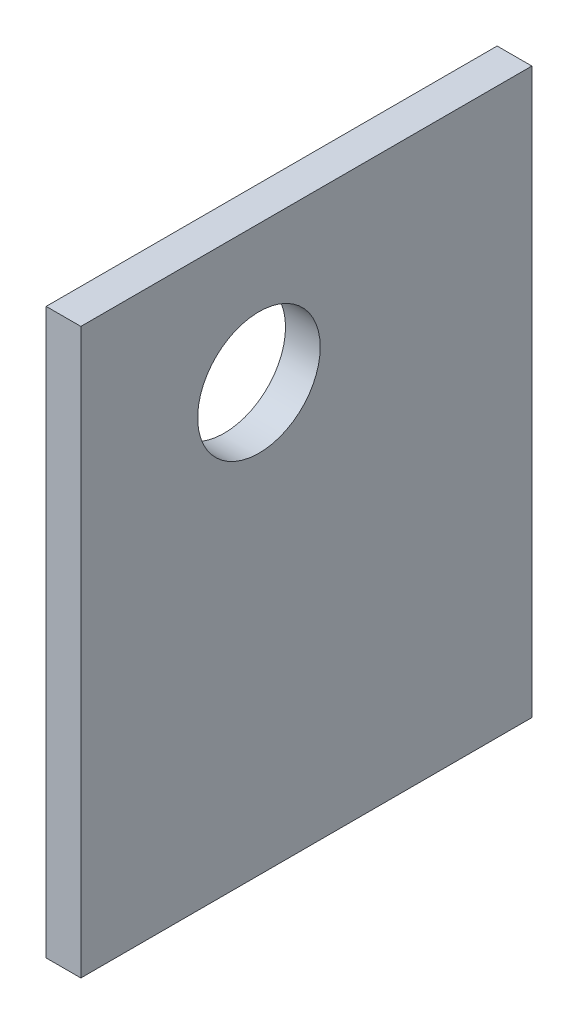
SolidWorks part; units mm, degrees
ref_plane "Alzado" through (0, 0, 0) normal (1, 0, 0) x (0, 1, 0)
ref_plane "Planta" through (0, 0, 0) normal (0, 0, 1) x (0, 1, 0)
ref_plane "Vista lateral" through (0, 0, 0) normal (0, 1, 0) x (-1, 0, 0)
sketch "Croquis2" plane through (0, 0, 0) normal (1, 0, 0) x (0, 1, 0)
  line L0 (-130.1333, 118) -> (369.3889, 118) construction
  line L1 (0, 0) -> (244, 0)
  line L2 (0, 0) -> (0, 195)
  line L3 (0, 195) -> (244, 195)
  line L4 (244, 0) -> (244, 195)
  line L5 (184.5, 257.2167) -> (184.5, -53.2056) construction
  circle A0 centre (184.5, 118) radius 26.5
  point P11 (184.5, 118)
  dimension "D5" = 53
  dimension "D1" = 244
  dimension "D2" = 195
  dimension "D3" = 77
  dimension "D4" = 59.5
extrude "Saliente-Extruir1" add sketch "Croquis2" along normal blind 15
